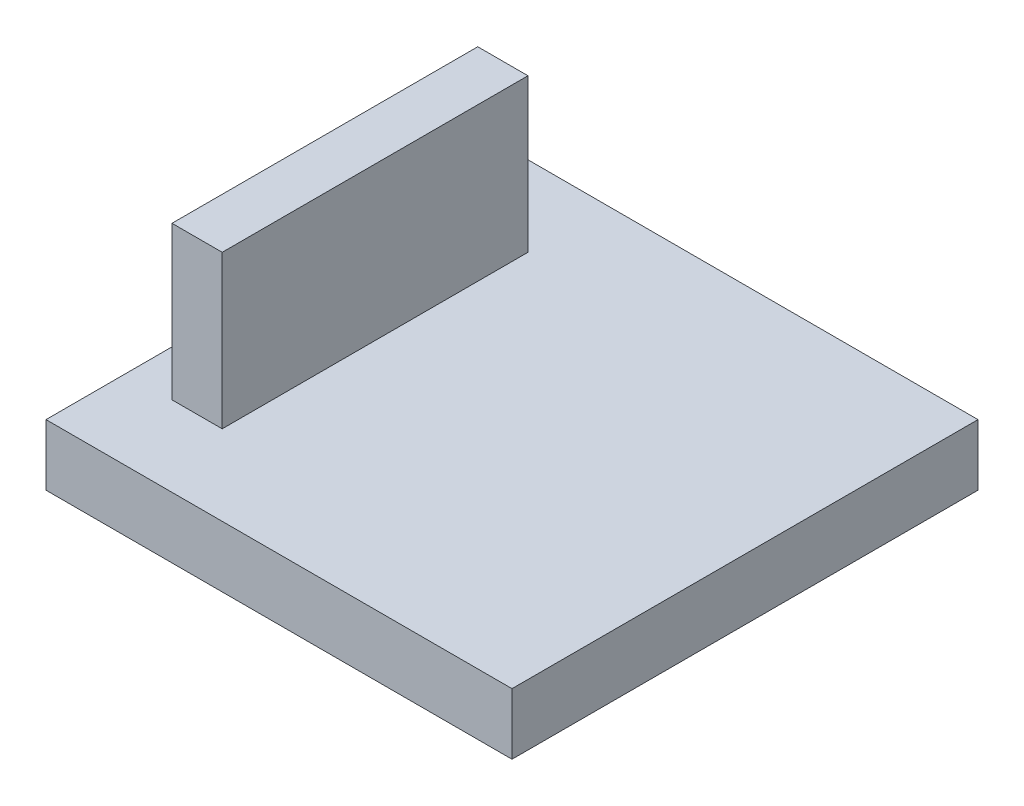
SolidWorks part; units mm, degrees
ref_plane "Front" through (0, 0, 0) normal (0, 0, 1) x (1, 0, 0)
ref_plane "Top" through (0, 0, 0) normal (0, 1, 0) x (1, 0, 0)
ref_plane "Right" through (0, 0, 0) normal (1, 0, 0) x (0, 0, -1)
sketch "草图1" plane through (0, 0, 0) normal (0, 1, 0) x (1, 0, 0)
  line L1 (0, 0) -> (15.24, 0)
  line L2 (0, 0) -> (0, 15.24)
  line L3 (0, 15.24) -> (15.24, 15.24)
  line L4 (15.24, 0) -> (15.24, 15.24)
  dimension "D1" = 15.24
  dimension "D2" = 15.24
extrude "凸台-拉伸1" add sketch "草图1" along normal blind 2
sketch "草图2" plane through (0, 2, 0) normal (0, 1, 0) x (1, 0, 0)
  line L0 (0, 15.24) -> (0, 0) construction
  line L1 (1.5, 12.62) -> (3.1426, 12.62)
  line L2 (1.5, 12.62) -> (1.5, 2.62)
  line L3 (1.5, 2.62) -> (3.1426, 2.62)
  line L4 (3.1426, 12.62) -> (3.1426, 2.62)
  point P4 (1.5, 7.62)
  point P7 (0, 7.62)
  dimension "D1" = 10
  dimension "D2" = 0
  dimension "D3" = 1.5
extrude "凸台-拉伸2" add sketch "草图2" along normal blind 5
